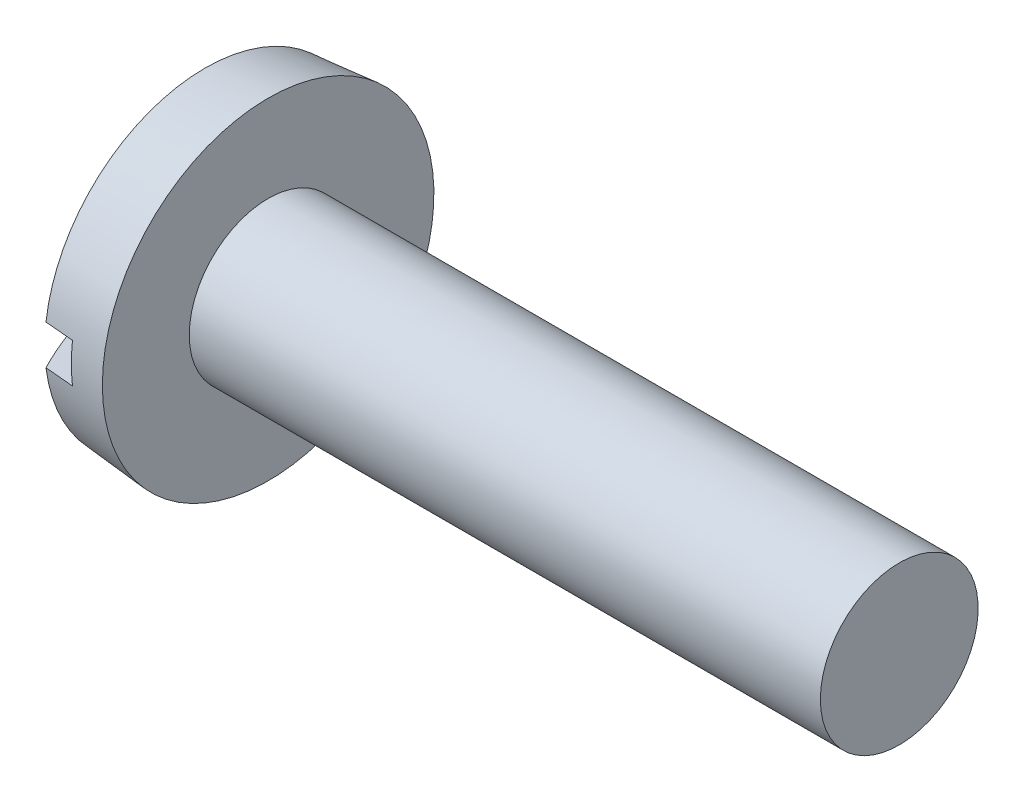
SolidWorks part; units mm, degrees
ref_plane "Plane1" through (0, 0, 0) normal (0, 0, 1) x (1, 0, 0)
ref_plane "Plane2" through (0, 0, 0) normal (0, 1, 0) x (1, 0, 0)
ref_plane "Plane3" through (0, 0, 0) normal (1, 0, 0) x (0, 0, -1)
sketch "BodySke" plane through (0, 0, 0) normal (0, 0, 1) x (1, 0, 0)
  line L0 (6.1976, 4.7625) -> (6.1976, 10.0076)
  line L1 (6.1976, 10.0076) -> (2.3876, 9.6743)
  line L2 (-25.4, 0) -> (127, 0) construction
  line L3 (6.1976, -10.0076) -> (2.3876, -9.6743) construction
  line L4 (6.1976, 4.7625) -> (44.2976, 4.7625)
  line L5 (44.2976, 4.7625) -> (44.2976, 0)
  line L6 (44.2976, 0) -> (0, 0)
  line L7 (6.1976, -4.7625) -> (44.2976, -4.7625) construction
  line L8 (7.7851, 6.35) -> (7.7851, -3.175) construction
  line L9 (18.8976, 6.35) -> (18.8976, -3.175) construction
  arc A0 (0, 0) -> (2.3876, 9.6743) centre (20.7933, 0) cw
  dimension "Head_ang" = 85
  dimension "Oval_ht" = 2.3876
  dimension "Head_ht" = 6.1976
  dimension "Diameter" = 9.525
  dimension "Length" = 38.1
  dimension "Head_dia" = 20.0152
  dimension "Advance" = 1.5875
  dimension "Thread_nom" = 25.4
revolve "Base-Revolve" add sketch "BodySke" angle 360 about L2
cosmetic thread "ThreadCosmetic" [suppressed] parameters "Thread_length"=25.4, "Thread_minor"=7.9375
sketch "Sketch2" plane through (0, 0, 0) normal (1, 0, 0) x (0, 0, -1)
  line L0 (10.0076, -1.1938) -> (10.0076, 1.1938)
  line L1 (10.0076, 1.1938) -> (-10.0076, 1.1938)
  line L2 (-10.0076, 1.1938) -> (-10.0076, -1.1938)
  line L3 (-10.0076, -1.1938) -> (10.0076, -1.1938)
  dimension "D1" = 20.0152
  dimension "D2" = 10.0076
  dimension "D3" = 1.1938
  dimension "Slot_width" = 2.3876
extrude "Slot" cut sketch "Sketch2" along normal blind 4.1402
sketch "Sketch3" plane through (0, 0, 0) normal (1, 0, 0) x (0, 0, -1)
  line L0 (-1.0287, 6.096) -> (1.0287, 6.096)
  line L1 (1.0287, 6.096) -> (1.0287, -6.096)
  line L2 (1.0287, -6.096) -> (-1.0287, -6.096)
  line L3 (-1.0287, -6.096) -> (-1.0287, 6.096)
  dimension "Cross_width" = 2.0574
  dimension "D1" = 1.0287
  dimension "Cross_dia" = 12.192
  dimension "D2" = 6.096
ref_plane "Plane4" through (7.2644, 0, 0) normal (1, 0, 0) x (0, 0, -1)
sketch "Sketch4" plane through (7.2644, 0, 0) normal (1, 0, 0) x (0, 0, -1)
  line L0 (-0.5143, 0.5143) -> (0.5143, 0.5143)
  line L1 (0.5143, 0.5143) -> (0.5144, -0.5143)
  line L2 (0.5144, -0.5143) -> (-0.5143, -0.5144)
  line L3 (-0.5143, -0.5144) -> (-0.5143, 0.5143)
  dimension "D1" = 1.0287
  dimension "D2" = 0.5143
  dimension "D3" = 1.0287
  dimension "D4" = 0.5143
loft "Cross" cut profiles "Sketch3", "Sketch4"
pattern_circular "CirPattern1" count 2 every 90 about axis through (0, 0, 0) along (1, 0, 0) of "Cross"
sketch "ThdSchSke" plane through (0, 0, 0) normal (0, 0, 1) x (1, 0, 0)
  line L0 (18.8976, -3.9688) -> (18.3418, -4.7625)
  line L1 (18.8976, -3.9688) -> (19.4534, -4.7625)
  line L2 (19.4534, -4.7625) -> (19.4534, -5.9531)
  line L3 (-3.175, 0) -> (5.1513, 0) construction
  line L5 (19.4534, -5.9531) -> (18.3418, -5.9531)
  line L6 (18.3418, -5.9531) -> (18.3418, -4.7625)
  dimension "Diameter" = 9.525
  dimension "SideAngle" = 55
  dimension "VeeAngle" = 70
  dimension "Thread_minor" = 7.9375
  dimension "Overcut" = 11.9063
  dimension "Start" = 18.8976
revolve "ThreadSchematic" [suppressed] cut sketch "ThdSchSke" angle 360 about L3
pattern_linear "ThdSchPat" [suppressed]
equation "\"D1@Sketch3\" = \"Cross_width@Sketch3\" / 2"
equation "\"D2@Sketch3\" = \"Cross_dia@Sketch3\" / 2"
equation "\"D1@Sketch4\" = \"Cross_width@Sketch3\"*.5"
equation "\"D2@Sketch4\" = \"D1@Sketch4\" / 2"
equation "\"D3@Sketch4\" = \"D1@Sketch4\""
equation "\"D4@Sketch4\" = \"D2@Sketch4\""
equation "\"D1@Sketch2\" = \"Head_dia@BodySke\""
equation "\"D2@Sketch2\" = \"D1@Sketch2\" / 2"
equation "\"D3@Sketch2\" = \"Slot_width@Sketch2\" / 2"
equation "\"Thread_length@ThreadCosmetic\" = ((sgn( (\"Length@BodySke\" - \"Advance@BodySke\" ) - \"Thread_nom@BodySke\" )-1)*( (\"Length@BodySke\" - \"Advance@BodySke\" ) - \"Thread_nom@BodySke\" ))/-2+ \"Thread_nom@BodySke\""
equation "\"Thread_minor@ThdSchSke\" = \"Thread_minor@ThreadCosmetic\""
equation "\"Diameter@ThdSchSke\" = \"Diameter@BodySke\""
equation "\"Overcut@ThdSchSke\" = \"Diameter@BodySke\" * 1.25"
equation "\"Start@ThdSchSke\" = \"Head_ht@BodySke\" + \"Length@BodySke\" - \"Thread_length@ThreadCosmetic\"  '---Non-countersunk---"
equation "\"Num_threads@ThdSchPat\" = int( \"Thread_length@ThreadCosmetic\" / \"Advance@BodySke\" + 0.999 )  + 1"
equation "\"Advance@ThdSchPat\" = \"Thread_length@ThreadCosmetic\" /  (\"Num_threads@ThdSchPat\" - 1) 'relax it"
